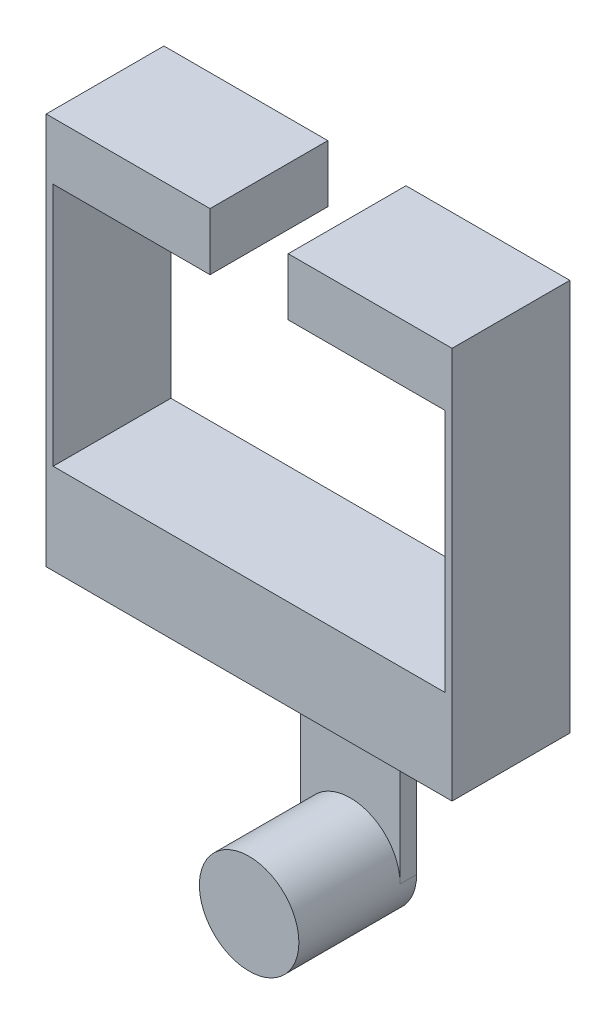
SolidWorks part; units mm, degrees
material "Ti-6Al-4VSolution treated and aged (SS)"
ref_plane "Front Plane" through (0, 0, 0) normal (0, 0, 1) x (1, 0, 0)
ref_plane "Top Plane" through (0, 0, 0) normal (0, 1, 0) x (1, 0, 0)
ref_plane "Right Plane" through (0, 0, 0) normal (1, 0, 0) x (0, 0, -1)
sketch "Sketch2" plane through (0, 0, 0) normal (0, 0, 1) x (1, 0, 0)
  circle A0 centre (0, 0) radius 8.0498
  dimension "D1" = 16.0996
extrude "Boss-Extrude1" add sketch "Sketch2" along normal blind 19.05 contours A0
sketch "Sketch3" plane through (0, 0, 0) normal (0, 0, -1) x (-1, 0, 0)
  line L0 (-11.1586, 0) -> (11.9199, 0) construction
  line L2 (-8.0498, 0) -> (8.0498, 0)
  line L3 (-8.0498, 0) -> (-8.0498, 32.1991)
  line L4 (-8.0498, 32.1991) -> (8.0498, 32.1991)
  line L5 (8.0498, 0) -> (8.0498, 32.1991)
  circle A0 centre (0, 0) radius 8.0498 construction
  point P3 (-8.0498, 0)
  point P4 (8.0498, 0)
  dimension "D1" = 32.1991
extrude "Boss-Extrude2" add sketch "Sketch3" against normal blind 2.6715 contours L3 L4 L5 L2
sketch "Sketch4" plane through (0, 32.1991, 0) normal (0, 1, 0) x (1, 0, 0)
  line L0 (-16.3312, 0) -> (11.4009, 0) construction
  line L1 (0, -19.05) -> (0, 8.3317) construction
  line L2 (-31.7043, 0) -> (31.7043, 0)
  line L3 (-31.7043, 0) -> (-31.7043, -19.05)
  line L4 (-31.7043, -19.05) -> (31.7043, -19.05)
  line L5 (31.7043, 0) -> (31.7043, -19.05)
  point P9 (0, 0)
  point P10 (37.7229, 0)
  point P11 (0, 0)
  point P12 (11.4009, 0)
  point P13 (0, -19.05)
  dimension "D1" = 63.4086
  dimension "D2" = 19.05
extrude "Boss-Extrude3" add sketch "Sketch4" along normal blind 14.6541
ref_plane "Plane1" through (0, 0, 0) normal (1, 0, 0) x (0, 0, -1)
sketch "Sketch5" plane through (31.7043, 0, 0) normal (1, 0, 0) x (0, 0, -1)
  line L0 (0, 46.8532) -> (0, 32.1991) construction
  line L1 (-19.05, 32.1991) -> (0, 32.1991)
  line L2 (-19.05, 32.1991) -> (-19.05, 86.3733)
  line L3 (-19.05, 86.3733) -> (0, 86.3733)
  line L4 (0, 32.1991) -> (0, 86.3733)
  dimension "D1" = 54.1742
extrude "Boss-Extrude4" add sketch "Sketch5" along normal blind 1.1289
mirror "Mirror1" about plane through (0, 0, 0) normal (1, 0, 0) of "Boss-Extrude4"
sketch "Sketch6" plane through (0, 86.3733, 0) normal (0, 1, 0) x (1, 0, 0)
  line L0 (31.7043, 0) -> (-31.7043, 0) construction
  line L1 (32.8332, -19.05) -> (6.3246, -19.05)
  line L2 (32.8332, -19.05) -> (32.8332, 0)
  line L3 (32.8332, 0) -> (6.3246, 0)
  line L4 (6.3246, -19.05) -> (6.3246, 0)
  dimension "D1" = 26.5086
extrude "Boss-Extrude5" add sketch "Sketch6" along normal blind 9.2711
mirror "Mirror2" about plane through (0, 0, 0) normal (1, 0, 0) of "Boss-Extrude4", "Boss-Extrude5"
equation "\"L\"= 0.75'length of feature A"
equation "\"Sy\"= 120000'psi (ult strength)"
equation "\"E\"= 15200000'psi (youngs M)"
equation "\"F\"= 800'lbf (load, per side)"
equation "\"SF\"= 5'Factor of safety"
equation "\"SySf\"= \"Sy\" / \"SF\"'psi (factor of safety ult strength)"
equation "\"d\"= ( ( \"L\" * \"F\" * 16 * 2 ) / ( \"SySf\" * pi ) ) ^ ( 1 / 3 )'Diam feat A"
equation "\"D1@Sketch2\"=\"d\""
equation "\"D1@Boss-Extrude1\"=\"L\""
equation "\"highB\"= 2 * \"d\"'height feat B"
equation "\"depthB\"= ( \"F\" * 2 ) / ( \"SySf\" * \"d\" )'depth feat B"
equation "\"D1@Sketch3\"=\"highB\""
equation "\"D1@Boss-Extrude2\"=\"depthB\""
equation "\"width A T\"= 0.498'Width feature a t beam"
equation "\"width B T\"= 0.9992'width feature b t beam"
equation "\"total width t\"= \"width A T\" + \"width B T\" * 2'total width t beam"
equation "\"D1@Sketch4\"=\"total width t\""
equation "\"D2@Sketch4\"=\"L\""
equation "\"highC\"= sqr ( ( \"F\" * \"total width t\" * 2 * 3 ) / ( \"L\" * \"SySf\" * 2 ) )'height feat C"
equation "\"D1@Boss-Extrude3\"=\"highC\""
equation "\"highD\"= 1.499'Height feat d (t beam C)"
equation "\"widthD\"= ( \"F\" / ( \"L\" * \"SySf\" ) )'width feat d"
equation "\"D1@Sketch5\"=\"d\"+\"highD\""
equation "\"D1@Boss-Extrude4\"=\"widthD\""
equation "\"Length E total\"= ( \"width B T\" + \"widthD\" )'Total length of E"
equation "\"height E\"= sqr ( ( \"F\" * \"width B T\" * 3 ) / ( \"L\" * \"SySf\" ) )'height feat E"
equation "\"D1@Sketch6\"=\"Length E total\""
equation "\"D1@Boss-Extrude5\"=\"height E\""
